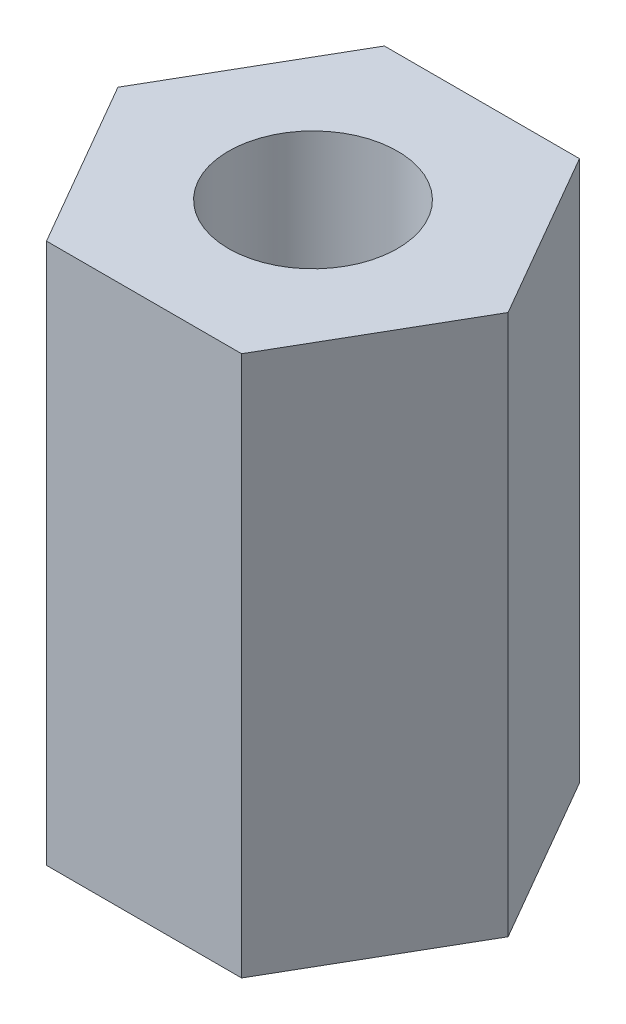
SolidWorks part; units mm, degrees
material "ABS"
ref_plane "前视基准面" through (0, 0, 0) normal (0, 0, 1) x (1, 0, 0)
ref_plane "上视基准面" through (0, 0, 0) normal (0, 1, 0) x (1, 0, 0)
ref_plane "右视基准面" through (0, 0, 0) normal (1, 0, 0) x (0, 0, -1)
sketch "草图1" plane through (0, 0, 0) normal (0, 1, 0) x (1, 0, 0)
  line L1 (1.4434, -2.5) -> (2.8868, 0)
  line L2 (2.8868, 0) -> (1.4434, 2.5)
  line L3 (1.4434, 2.5) -> (-1.4434, 2.5)
  line L4 (-1.4434, 2.5) -> (-2.8868, 0)
  line L5 (-2.8868, 0) -> (-1.4434, -2.5)
  line L6 (-1.4434, -2.5) -> (1.4434, -2.5)
  circle A0 centre (0, 0) radius 1.25
  circle A1 centre (0, 0) radius 2.5 construction
  dimension "D1" = 2.5
  dimension "D2" = 5
extrude "凸台-拉伸1" add sketch "草图1" along normal blind 8
